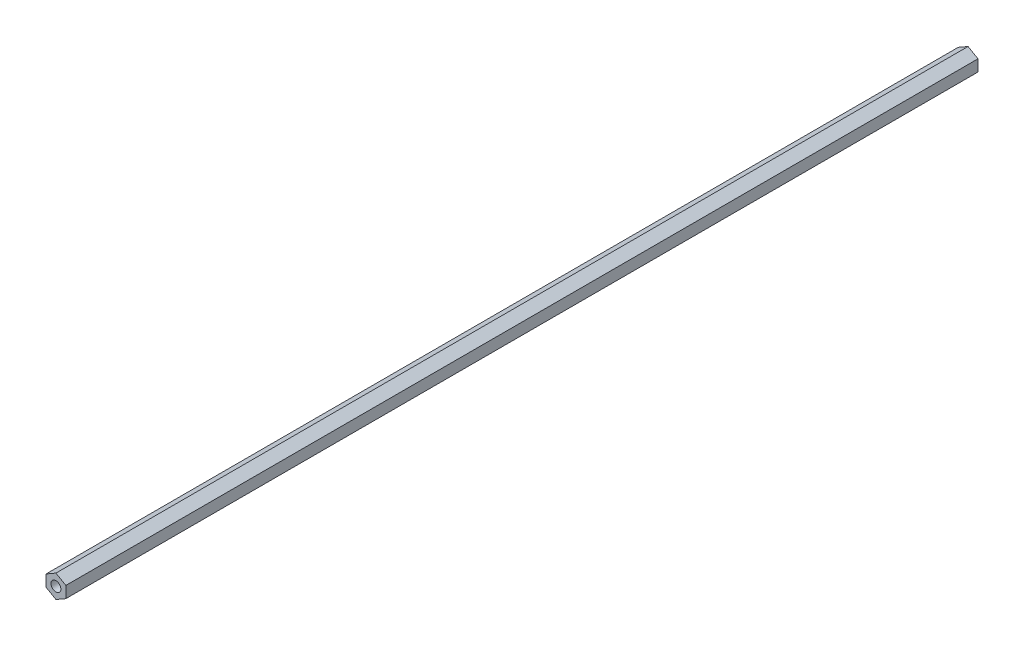
SolidWorks part; units mm, degrees
ref_plane "Front Plane" through (0, 0, 0) normal (0, 0, 1) x (1, 0, 0)
ref_plane "Top Plane" through (0, 0, 0) normal (0, 1, 0) x (1, 0, 0)
ref_plane "Right Plane" through (0, 0, 0) normal (1, 0, 0) x (0, 0, -1)
sketch "Sketch1" plane through (0, 0, 0) normal (0, 0, 1) x (1, 0, 0)
  line L1 (0, 7.3323) -> (-6.35, 3.6662) construction
  line L2 (-6.35, 3.6662) -> (-6.35, -3.6662) construction
  line L3 (-6.35, -3.6662) -> (0, -7.3323) construction
  line L4 (0, -7.3323) -> (6.35, -3.6662) construction
  line L5 (6.35, -3.6662) -> (6.35, 3.6662) construction
  line L6 (6.35, 3.6662) -> (0, 7.3323) construction
  circle A2 centre (0, 0) radius 6.35 construction
  dimension "Width" = 12.7
sketch "Sketch2" plane through (0, 0, 0) normal (1, 0, 0) x (0, 0, -1)
  line L0 (-292.1, 7.3323) -> (292.1, 7.3323) construction
  point P2 (0, 7.3323)
  point P3 (260.35, 7.3323)
  point P4 (-260.35, 7.3323)
  dimension "Length" = 584.2
  dimension "D2" = 31.75
  dimension "D1" = 31.75
sketch "Sketch3" plane through (0, 0, 0) normal (0, 0, 1) x (1, 0, 0)
  line L0 (-6.35, -3.6662) -> (0, -7.3323) construction
  line L1 (0, -7.3323) -> (6.35, -3.6662) construction
  line L2 (6.35, -3.6662) -> (6.35, 3.6662) construction
  line L3 (6.35, 3.6662) -> (0, 7.3323) construction
  line L4 (0, 7.3323) -> (-6.35, 3.6662) construction
  line L5 (-6.35, 3.6662) -> (-6.35, -3.6662) construction
  line L6 (-6.35, -3.6662) -> (0, -7.3323)
  line L7 (0, -7.3323) -> (6.35, -3.6662)
  line L8 (6.35, -3.6662) -> (6.35, 3.6662)
  line L9 (6.35, 3.6662) -> (0, 7.3323)
  line L10 (0, 7.3323) -> (-6.35, 3.6662)
  line L11 (-6.35, 3.6662) -> (-6.35, -3.6662)
extrude "Boss-Extrude2" add sketch "Sketch3" along normal up to vertex (292.1 mm away) and the other way up to vertex (292.1 mm away) up to point (0, 7.3323, 292.1) other way up to point (0, 7.3323, -292.1)
sketch "Sketch4" plane through (0, 0, 292.1) normal (0, 0, 1) x (1, 0, 0)
  point P0 (0, 0)
hole_wizard "1/4 (0.25) Diameter Hole1" positions "Sketch5" profile "Sketch6" hole size "1/4" standard "ANSI Inch"
sketch "Sketch5" plane through (0, 0, 292.1) normal (0, 0, 1) x (1, 0, 0)
  point P0 (0, 0)
sketch "Sketch6" plane through (0, 0, 292.1) normal (1, 0, 0) x (0, -1, 0)
  line L0 (0, 0) -> (0, 27.3077)
  line L1 (0, 27.3077) -> (3.175, 25.4)
  line L2 (3.175, 25.4) -> (3.175, 0)
  line L5 (3.175, 0) -> (0, 0)
  line L10 (0, 27.3077) -> (-3.175, 25.4) construction
  line L11 (0, -6.35) -> (0, 107.95) construction
  dimension "Hole Dia." = 6.35
  dimension "Hole Depth" = 25.4
  dimension "Drill Angle" = 118
hole_wizard "1/4 (0.25) Diameter Hole2" positions "Sketch7" profile "Sketch8" hole size "1/4" standard "ANSI Inch"
sketch "Sketch7" plane through (0, 0, -292.1) normal (0, 0, -1) x (-1, 0, 0)
  point P0 (0, 0)
sketch "Sketch8" plane through (0, 0, -292.1) normal (1, 0, 0) x (0, 1, 0)
  line L0 (0, 0) -> (0, 27.3077)
  line L1 (0, 27.3077) -> (3.175, 25.4)
  line L2 (3.175, 25.4) -> (3.175, 0)
  line L5 (3.175, 0) -> (0, 0)
  line L10 (0, 27.3077) -> (-3.175, 25.4) construction
  line L11 (0, -6.35) -> (0, 107.95) construction
  dimension "Hole Dia." = 6.35
  dimension "Hole Depth" = 25.4
  dimension "Drill Angle" = 118
equation "\"D2@Sketch2\" = \"D1@Sketch2\""
equation "\"D1@Sketch2\" = \"Width@Sketch1\" * 2.5"
